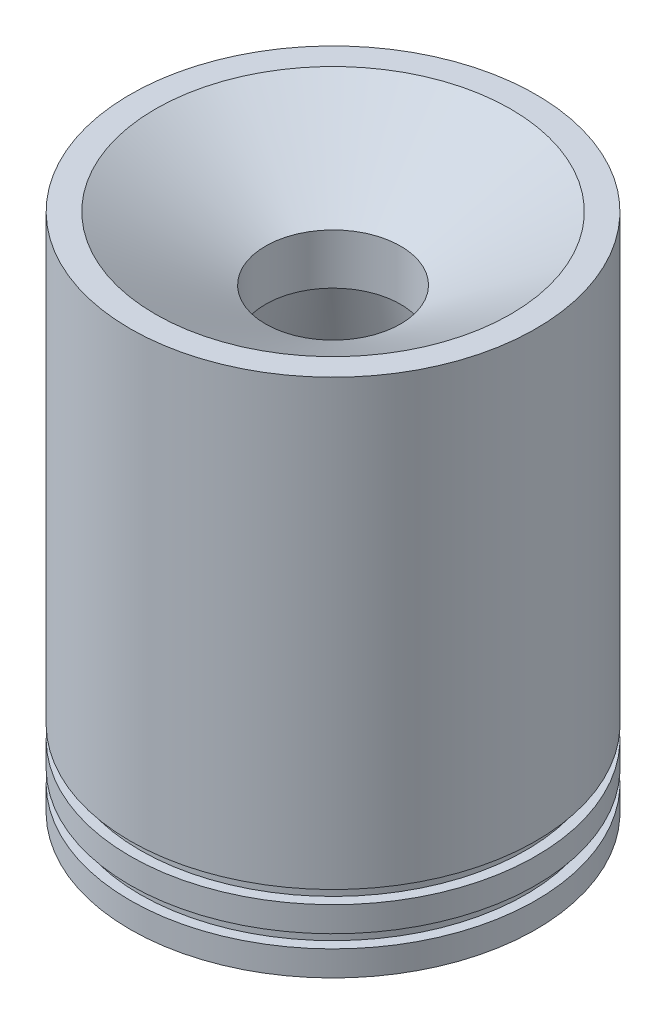
SolidWorks part; units mm, degrees
ref_plane "Front Plane" through (0, 0, 0) normal (0, 0, 1) x (1, 0, 0)
ref_plane "Top Plane" through (0, 0, 0) normal (0, 1, 0) x (1, 0, 0)
ref_plane "Right Plane" through (0, 0, 0) normal (1, 0, 0) x (0, 0, -1)
sketch "Sketch1" plane through (0, 0, 0) normal (0, 0, 1) x (1, 0, 0)
  line L0 (-51.1302, 0) -> (-51.1302, -111.8021)
  line L1 (-51.1302, -131.1061) -> (-44.45, -131.1061)
  line L2 (-44.45, -131.1061) -> (-17.018, -28.7285)
  line L3 (-17.018, -28.7285) -> (-17.018, -16.0285)
  line L4 (-17.018, -16.0285) -> (-44.7802, 0)
  line L5 (-44.7802, 0) -> (-51.1302, 0)
  line L6 (0, 0) -> (0, -59.8568) construction
  line L7 (-51.1302, -131.1061) -> (-51.1302, -124.7561)
  line L8 (-51.1302, -124.7561) -> (-48.5902, -124.7561)
  line L9 (-48.5902, -124.7561) -> (-48.5902, -121.4541)
  line L10 (-48.5902, -121.4541) -> (-51.1302, -121.4541)
  line L11 (-51.1302, -121.4541) -> (-51.1302, -115.1041)
  line L12 (-51.1302, -115.1041) -> (-48.5902, -115.1041)
  line L13 (-48.5902, -115.1041) -> (-48.5902, -111.8021)
  line L14 (-48.5902, -111.8021) -> (-51.1302, -111.8021)
  dimension "D1" = 17.018
  dimension "D2" = 51.1302
  dimension "D3" = 44.45
  dimension "D4" = 15
  dimension "D5" = 60
  dimension "D6" = 6.35
  dimension "D7" = 12.7
  dimension "D8" = 3.302
  dimension "D9" = 2.54
  dimension "D10" = 6.35
  dimension "D11" = 3.302
  dimension "D12" = 6.35
revolve "Revolve1" add sketch "Sketch1" angle 360 about L6
equation "\"D11@Sketch1\"=\"D8@Sketch1\""
